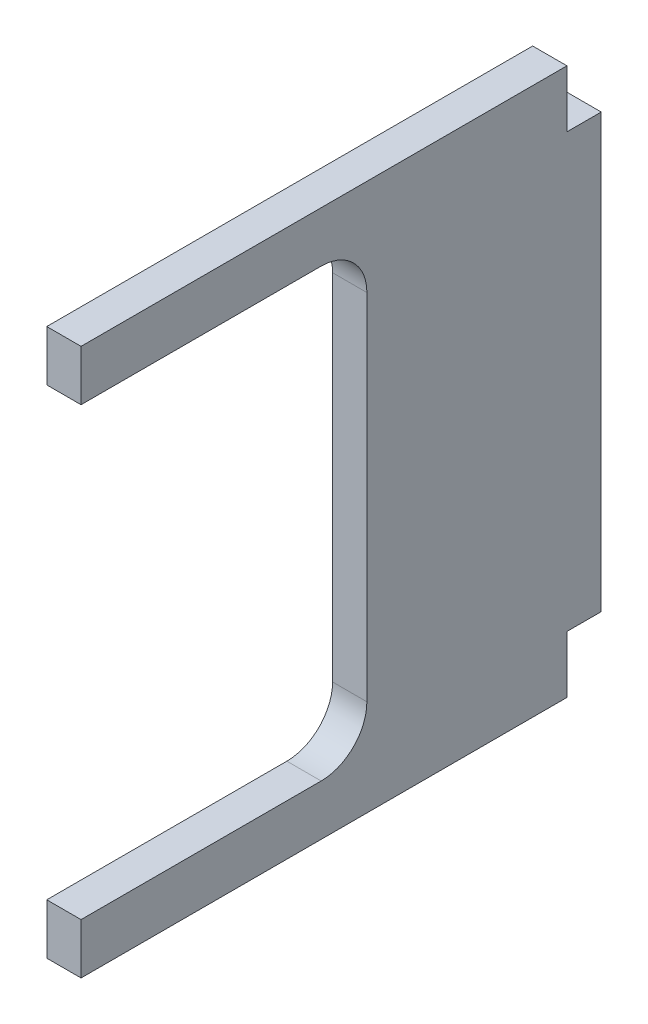
SolidWorks part; units mm, degrees
material "PVC rigido"
ref_plane "Piano frontale" through (0, 0, 0) normal (0, 0, 1) x (1, 0, 0)
ref_plane "Piano superiore" through (0, 0, 0) normal (0, 1, 0) x (1, 0, 0)
ref_plane "Piano destro" through (0, 0, 0) normal (1, 0, 0) x (0, 0, -1)
sketch "Schizzo1" plane through (0, 0, 0) normal (0, 0, 1) x (1, 0, 0)
  line L0 (-223.5, 18.9239) -> (-223.5, -18.9239) construction
  line L1 (-223.5, 18.9239) -> (-223.5, -18.9239)
  line L3 (-226.5, -18.9239) -> (-226.5, 18.9239) construction
  line L4 (-223.5, -18.9239) -> (-226.5, -18.9239) construction
  line L5 (-226.5, 18.9239) -> (-223.5, 18.9239)
  line L6 (-226.5, -18.9239) -> (-226.5, 18.9239)
  line L7 (-223.5, -18.9239) -> (-226.5, -18.9239)
extrude "Estrusione-Estrusione1" add sketch "Schizzo1" along normal up to surface (17.5 mm away) and the other way up to surface (3 mm away)
ref_plane "Piano1" through (0, 0, 0) normal (0, 1, 0) x (1, 0, 0)
sketch "Schizzo2" plane through (0, 18.9239, 0) normal (0, 1, 0) x (1, 0, 0)
  line L0 (-223.5, -17.5) -> (-223.5, 3) construction
  line L1 (-226.5, 0) -> (-223.5, 0)
  line L2 (-226.5, 0) -> (-226.5, -42.5)
  line L3 (-226.5, -42.5) -> (-223.5, -42.5)
  line L4 (-223.5, 0) -> (-223.5, -42.5)
  line L5 (-233, -42.5) -> (-228.5, -42.5) construction
extrude "Estrusione-Estrusione2" add sketch "Schizzo2" along normal blind 5
sketch "Schizzo3" plane through (-223.5, 0, 0) normal (1, 0, 0) x (0, 0, -1)
  line L0 (-42.5, 23.9239) -> (-42.5, 18.9239) construction
  line L1 (-17.5, 18.9239) -> (-42.5, 18.9239)
  line L2 (-17.5, 18.9239) -> (-17.5, 19.5)
  line L3 (-17.5, 19.5) -> (-42.5, 19.5)
  line L4 (-42.5, 18.9239) -> (-42.5, 19.5)
  line L5 (-21.5, 19.5) -> (-42.5, 19.5) construction
extrude "Taglio-Estrusione1" cut sketch "Schizzo3" against normal blind 10
fillet "Raccordo1" radius 4 1 edges at (-225, 19.5, 17.5)
mirror "Specchia1" about plane through (0, 0, 0) normal (0, 1, 0) of "Estrusione-Estrusione2", "Taglio-Estrusione1", "Raccordo1"
